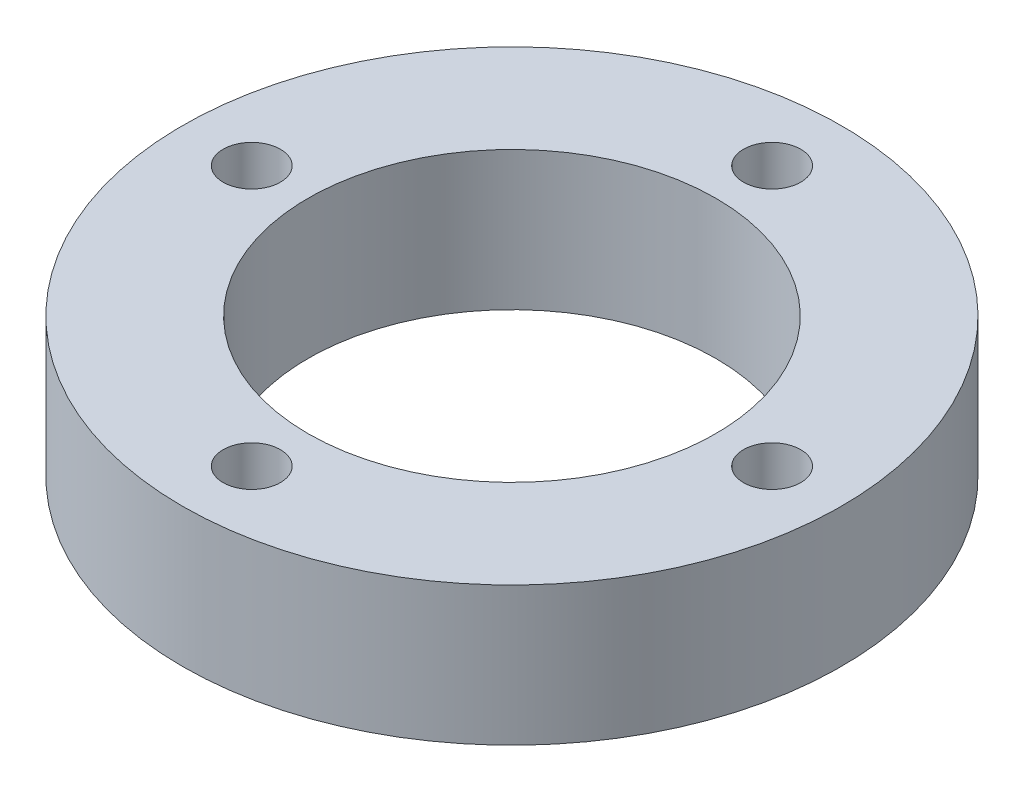
SolidWorks part; units mm, degrees
ref_plane "Front Plane" through (0, 0, 0) normal (0, 0, 1) x (1, 0, 0)
ref_plane "Top Plane" through (0, 0, 0) normal (0, 1, 0) x (1, 0, 0)
ref_plane "Right Plane" through (0, 0, 0) normal (1, 0, 0) x (0, 0, -1)
sketch "Sketch1" plane through (0, 0, 0) normal (0, 1, 0) x (1, 0, 0)
  circle A0 centre (0, 0) radius 38
  circle A1 centre (0, 0) radius 23.51
  circle A2 centre (-30, 0) radius 3.3
  circle A3 centre (30, 0) radius 3.3
  circle A4 centre (0, -30) radius 3.3
  circle A5 centre (0, 30) radius 3.3
extrude "Bearing_Carrier_Extrude" add sketch "Sketch1" along normal blind 16
equation "\"ValveDiameter\" = 50mm"
equation "\"MotorGearTeeth\" = 40"
equation "\"OutputGearTeeth\" = 80"
equation "\"GearModule\" = 1.5mm"
equation "\"PressureAngle\" = 20deg"
equation "\"GearCenterDistance\" = 90mm"
equation "\"GearWidth\" = 18mm"
equation "\"OutputShaftDiameter\" = 20mm"
equation "\"BearingOD\" = 47mm"
equation "\"BearingWidth\" = 14mm"
equation "\"PlateThickness\" = 6mm"
equation "\"ValveRotation\" = 90deg"
